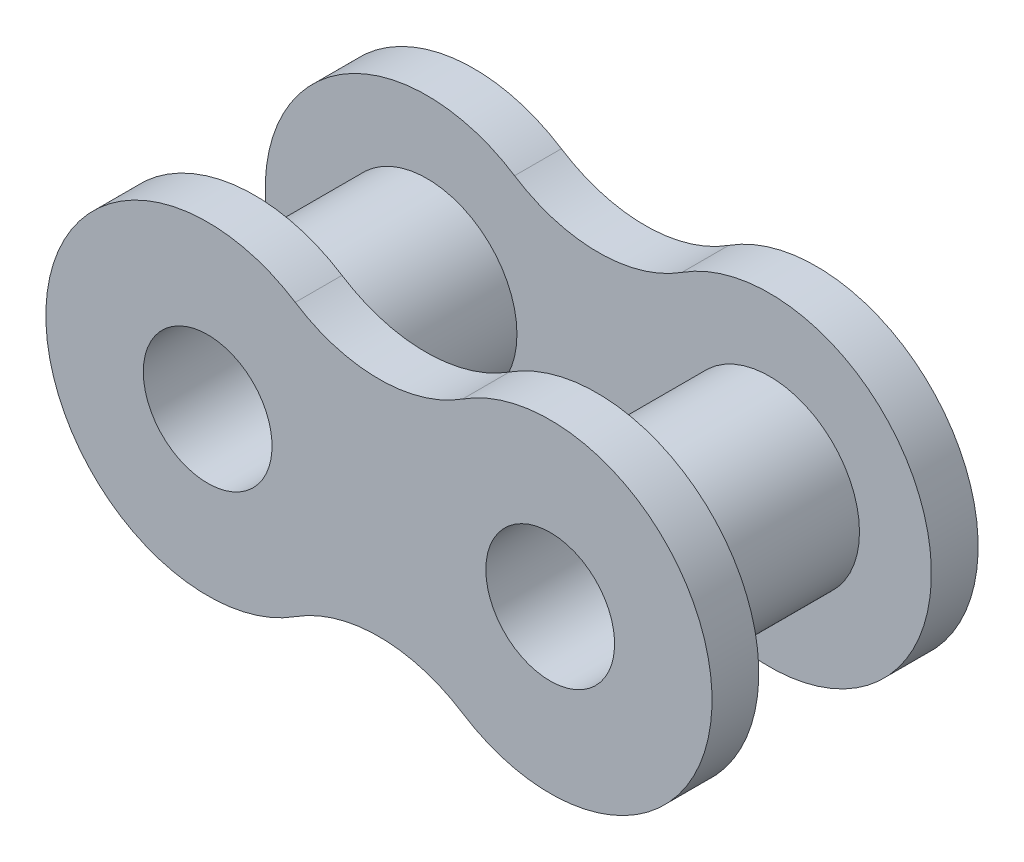
SolidWorks part; units mm, degrees
ref_plane "Alzado" through (0, 0, 0) normal (0, 0, 1) x (1, 0, 0)
ref_plane "Planta" through (0, 0, 0) normal (0, 1, 0) x (1, 0, 0)
ref_plane "Vista lateral" through (0, 0, 0) normal (1, 0, 0) x (0, 0, -1)
sketch "Sketch1" plane through (0, 0, 0) normal (0, 0, 1) x (1, 0, 0)
  line L0 (-9.2625, 0) -> (9.2625, 0) construction
  line L1 (0, 3.1) -> (0, -3.1) construction
  arc A0 (-2.3273, 3.7841) -> (-2.3273, -3.7841) centre (-4.7625, 0) ccw
  arc A1 (-2.3273, 3.7841) -> (2.3273, 3.7841) centre (0, 7.4005) ccw
  arc A2 (-2.3273, -3.7841) -> (2.3273, -3.7841) centre (0, -7.4005) cw
  arc A3 (2.3273, 3.7841) -> (2.3273, -3.7841) centre (4.7625, 0) cw
  point P4 (0, 0)
  point P10 (0, 0)
  dimension "D1" = 9
  dimension "D3" = 9.525
  dimension "D2" = 6.2
extrude "Boss-Extrude1" add sketch "Sketch1" along normal blind 1.3
sketch "Sketch2" plane through (0, 0, 1.3) normal (0, 0, 1) x (1, 0, 0)
  circle A0 centre (-4.7625, 0) radius 2.5
  circle A1 centre (4.7625, 0) radius 2.5
  circle A2 centre (-4.7625, 0) radius 1.79
  circle A3 centre (4.7625, 0) radius 1.79
  dimension "D1" = 5
  dimension "D2" = 3.58
ref_plane "Plane1" through (0, 0, 3.7) normal (0, 0, -1) x (-1, 0, 0)
extrude "Boss-Extrude2" add sketch "Sketch2" along normal blind 5
mirror "Mirror5" about plane through (0, 0, 3.7) normal (0, 0, -1) of "Boss-Extrude1"
sketch "Sketch4" plane through (0, 0, 3.7) normal (0, 0, -1) x (-1, 0, 0)
  circle A0 centre (-4.7625, 0) radius 1.79 construction
  circle A1 centre (4.7625, 0) radius 1.79 construction
  circle A2 centre (-4.7625, 0) radius 1.79
  circle A3 centre (4.7625, 0) radius 1.79
extrude "Cut-Extrude1" cut sketch "Sketch4" against normal through all both and the other way through all
